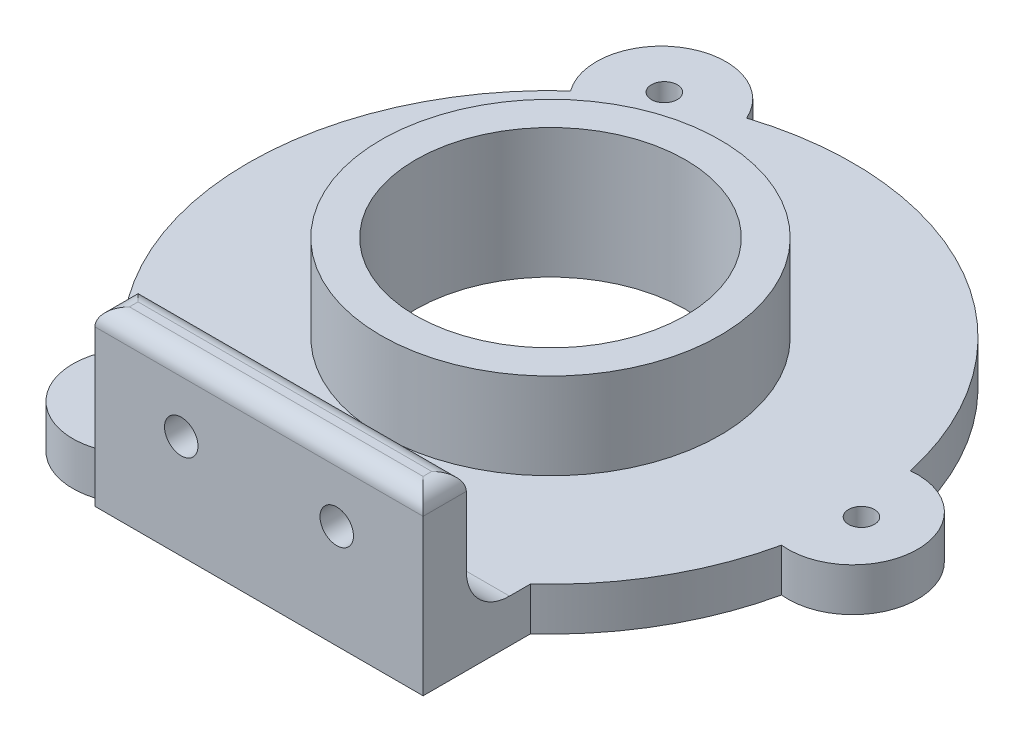
SolidWorks part; units mm, degrees
ref_plane "Front Plane" through (0, 0, 0) normal (0, 0, 1) x (1, 0, 0)
ref_plane "Top Plane" through (0, 0, 0) normal (0, 1, 0) x (1, 0, 0)
ref_plane "Right Plane" through (0, 0, 0) normal (1, 0, 0) x (0, 0, -1)
sketch "Sketch1" plane through (0, 0, 0) normal (0, 1, 0) x (1, 0, 0)
  circle A0 centre (0, 0) radius 28
  dimension "D1" = 56
extrude "Boss-Extrude1" add sketch "Sketch1" along normal blind 4
sketch "Sketch2" plane through (0, 4, 0) normal (0, 1, 0) x (1, 0, 0)
  circle A0 centre (28, 0) radius 6
  circle A2 centre (0, 0) radius 28 construction
  circle A3 centre (-14, -24.2487) radius 6
  circle A4 centre (-14, 24.2487) radius 6
  point P10 (0, 0)
  point P11 (0, 0)
  dimension "D1" = 12
  dimension "D2" = 3
extrude "Boss-Extrude2" add sketch "Sketch2" against normal blind 4
sketch "Sketch4" plane through (0, 4, 0) normal (0, 1, 0) x (1, 0, 0)
  circle A0 centre (28.8, 0) radius 1.1974
  arc A1 (27.3571, -5.9655) -> (27.3571, 5.9655) centre (28, 0) ccw construction
  circle A2 centre (-14.4, -24.9415) radius 1.1974
  circle A3 centre (-14.4, 24.9415) radius 1.1974
  point P11 (0, 0)
  dimension "D1" = 0
  dimension "D2" = 0.8
  dimension "D3" = 3
extrude "Cut-Extrude2" cut sketch "Sketch4" against normal through all
sketch "Sketch5" plane through (0, 4, 0) normal (0, 1, 0) x (1, 0, 0)
  circle A0 centre (0, 0) radius 12.5
  dimension "D1" = 25
extrude "Cut-Extrude3" cut sketch "Sketch5" against normal through all
sketch "Sketch6" plane through (0, 4, 0) normal (0, 1, 0) x (1, 0, 0)
  circle A0 centre (0, 0) radius 12.5
  circle A1 centre (0, 0) radius 15.7
  dimension "D1" = 3.2
extrude "Boss-Extrude3" add sketch "Sketch6" along normal blind 8
sketch "Sketch7" plane through (0, 4, 0) normal (0, 1, 0) x (1, 0, 0)
  line L1 (-11.55, -20.2487) -> (18.85, -20.2487)
  line L2 (-11.55, -20.2487) -> (-11.55, -30.6487)
  line L3 (-11.55, -30.6487) -> (18.85, -30.6487)
  line L4 (18.85, -20.2487) -> (18.85, -30.6487)
  arc A0 (-18.8448, -20.7092) -> (-8.5123, -26.6747) centre (-14, -24.2487) ccw construction
  dimension "D1" = 30.4
  dimension "D2" = 2.45
  dimension "D3" = 4
  dimension "D4" = 10.4
extrude "Boss-Extrude4" add sketch "Sketch7" against normal blind 4
sketch "Sketch8" plane through (0, 4, 0) normal (0, 1, 0) x (1, 0, 0)
  line L0 (-11.55, -29.7257) -> (-11.55, -30.6487) construction
  line L1 (18.85, -30.6487) -> (-11.55, -30.6487)
  line L2 (18.85, -30.6487) -> (18.85, -26.6487)
  line L3 (18.85, -26.6487) -> (-11.55, -26.6487)
  line L4 (-11.55, -30.6487) -> (-11.55, -26.6487)
  dimension "D1" = 4
extrude "Boss-Extrude5" add sketch "Sketch8" along normal blind 12
fillet "Fillet1" radius 4 1 edges at (3.65, 4, 26.6487)
fillet "Fillet2" radius 1.6 4 edges at (3.65, 16, 30.6487) (-11.55, 16, 28.6487) (3.65, 16, 26.6487) (18.85, 16, 28.6487)
sketch "Sketch9" plane through (0, 0, 30.6487) normal (0, 0, 1) x (1, 0, 0)
  line L0 (-11.55, 0) -> (-11.55, 14.4) construction
  line L1 (18.85, 0) -> (18.85, 14.4) construction
  line L2 (-9.95, 16) -> (17.25, 16) construction
  circle A0 centre (-3.55, 9.6) radius 1.55
  circle A1 centre (10.85, 9.6) radius 1.55
  dimension "D1" = 3.1
  dimension "D2" = 3.1
  dimension "D3" = 8
  dimension "D4" = 8
  dimension "D5" = 6.4
  dimension "D6" = 6.4
extrude "Cut-Extrude4" cut sketch "Sketch9" against normal blind 5
equation "\"D1@Sketch1\"=0.8*70"
equation "\"D1@Boss-Extrude1\"=0.8*5"
equation "\"D1@Boss-Extrude3\"=0.8*10"
equation "\"D1@Sketch7\"=0.8*38"
equation "\"D4@Sketch7\"=0.8*13"
equation "\"D4@Sketch9\"=\"D3@Sketch9\""
equation "\"D6@Sketch9\"=\"D5@Sketch9\""
